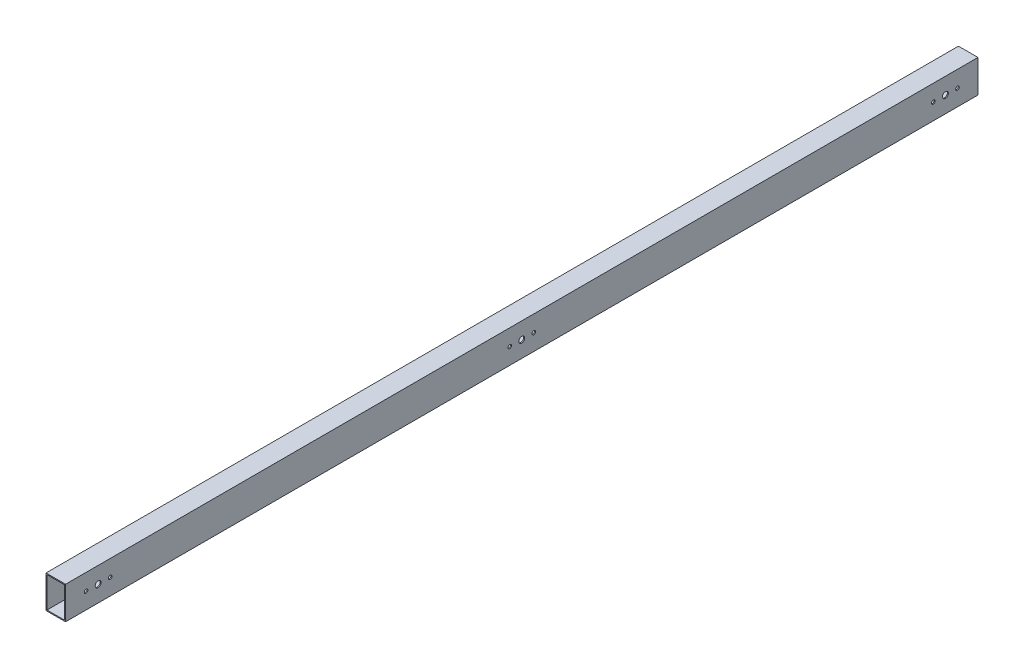
SolidWorks part; units mm, degrees
ref_plane "Plano frontal" through (0, 0, 0) normal (0, 0, 1) x (1, 0, 0)
ref_plane "Plano superior" through (0, 0, 0) normal (0, 1, 0) x (1, 0, 0)
ref_plane "Plano direito" through (0, 0, 0) normal (1, 0, 0) x (0, 0, -1)
sketch "Esboço1" plane through (0, 0, 0) normal (0, 0, 1) x (1, 0, 0)
  line L1 (0, 0) -> (30, 0)
  line L2 (0, 0) -> (0, 50)
  line L3 (0, 50) -> (30, 50)
  line L4 (30, 0) -> (30, 50)
  line L5 (1.5, 1.5) -> (28.5, 1.5)
  line L6 (1.5, 1.5) -> (1.5, 48.5)
  line L7 (1.5, 48.5) -> (28.5, 48.5)
  line L8 (28.5, 1.5) -> (28.5, 48.5)
  dimension "D1" = 50
  dimension "D2" = 30
  dimension "D3" = 1.5
  dimension "D4" = 1.5
  dimension "D5" = 1.5
  dimension "D6" = 1.5
extrude "Ressalto-extrusão1" add sketch "Esboço1" along normal blind 1400
sketch "Esboço2" plane through (30, 0, 0) normal (1, 0, 0) x (0, 0, -1)
  line L0 (-1350, 50) -> (-1350, 0) construction
  line L1 (-1400, 50) -> (0, 50) construction
  line L2 (-1400, 0) -> (0, 0) construction
  line L3 (-1580.4203, 25) -> (-1527.6135, 25) construction
  line L4 (-1400, 0) -> (-1400, 50) construction
  line L5 (-700, 50) -> (-700, 285.9274) construction
  line L6 (180.4203, 25) -> (127.6135, 25) construction
  line L7 (-50, 50) -> (-50, 0) construction
  line L8 (-700, 50) -> (-700, 0) construction
  line L9 (-825.3968, 25) -> (-761.7678, 25) construction
  point P6 (-1350, 25)
  point P19 (-68.5, 25)
  point P20 (-31.5, 25)
  point P21 (-1368.5, 25)
  point P22 (-1331.5, 25)
  point P23 (-50, 25)
  point P27 (-718.5, 25)
  point P28 (-681.5, 25)
  point P29 (-700, 25)
  dimension "D1" = 50
  dimension "D2" = 18.5
  dimension "D3" = 18.5
hole_wizard "Furo com folga de M52" positions "Esboço7" profile "Esboço6" hole size "M5" standard "ISO" end condition through all
sketch "Esboço7" plane through (30, 0, 0) normal (1, 0, 0) x (0, 0, -1)
  point P0 (-1368.5, 25)
  point P3 (-1331.5, 25)
  point P6 (-68.5, 25)
  point P9 (-31.5, 25)
  point P13 (-718.5, 25)
  point P16 (-681.5, 25)
sketch "Esboço6" plane through (30, 25, 1368.5) normal (0, 1, 0) x (0, 0, -1)
  line L0 (0, 0) -> (0, 30)
  line L1 (0, 30) -> (2.75, 30)
  line L2 (2.75, 30) -> (2.75, 0)
  line L5 (2.75, 0) -> (0, 0)
  line L11 (0, -6.35) -> (0, 107.95) construction
  dimension "Thru Hole Dia." = 5.5
  dimension "Thru Hole Depth" = 30
hole_wizard "Furo com folga de M81" positions "Esboço9" profile "Esboço10" hole size "M8" standard "ISO" end condition through all
sketch "Esboço9" plane through (30, 0, 0) normal (1, 0, 0) x (0, 0, -1)
  point P0 (-1350, 25)
  point P3 (-50, 25)
sketch "Esboço10" plane through (30, 25, 1350) normal (0, 1, 0) x (0, 0, -1)
  line L0 (0, 0) -> (0, 30)
  line L1 (0, 30) -> (4.5, 30)
  line L2 (4.5, 30) -> (4.5, 0)
  line L5 (4.5, 0) -> (0, 0)
  line L11 (0, -6.35) -> (0, 107.95) construction
  dimension "Thru Hole Dia." = 9
  dimension "Thru Hole Depth" = 30
hole_wizard "Furo com folga de M84" positions "Esboço18" profile "Esboço19" hole size "M8" standard "ISO"
sketch "Esboço18" plane through (30, 0, 0) normal (1, 0, 0) x (0, 0, -1)
  point P0 (-700, 25)
sketch "Esboço19" plane through (30, 25, 700) normal (0, 1, 0) x (0, 0, -1)
  line L0 (0, 0) -> (0, 1.5)
  line L1 (0, 1.5) -> (4.5, 1.5)
  line L2 (4.5, 1.5) -> (4.5, 0)
  line L5 (4.5, 0) -> (0, 0)
  line L11 (0, -6.35) -> (0, 107.95) construction
  dimension "Thru Hole Dia." = 9
  dimension "Thru Hole Depth" = 1.5
